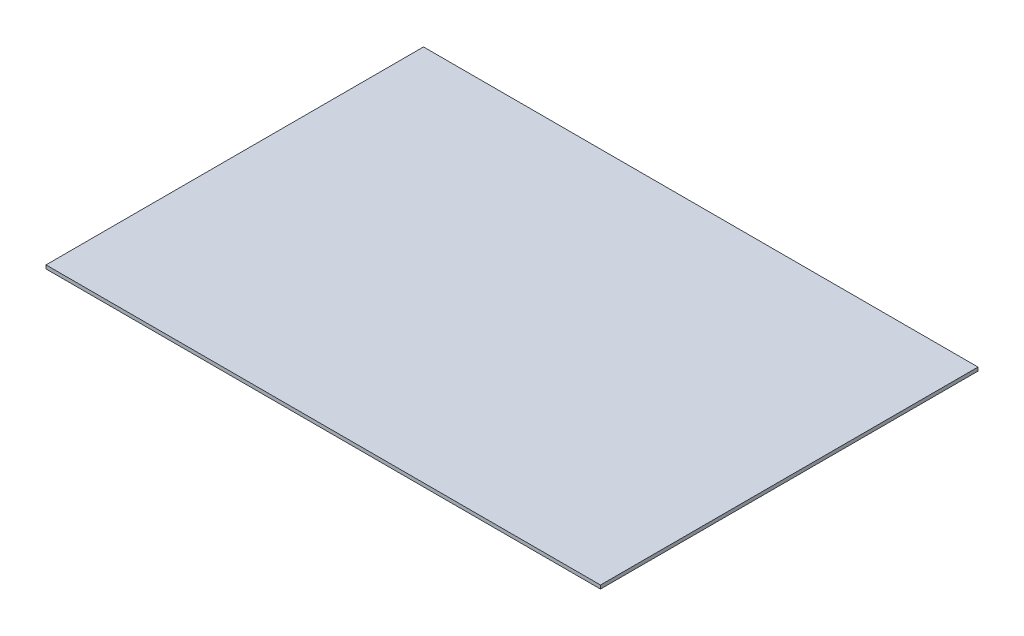
SolidWorks part; units mm, degrees
material "ABS PC"
ref_plane "Front Plane" through (0, 0, 0) normal (0, 0, 1) x (1, 0, 0)
ref_plane "Top Plane" through (0, 0, 0) normal (0, 1, 0) x (1, 0, 0)
ref_plane "Right Plane" through (0, 0, 0) normal (1, 0, 0) x (0, 0, -1)
sketch "Sketch1" plane through (0, 0, 0) normal (0, 1, 0) x (1, 0, 0)
  line L1 (0, 0) -> (940, 0)
  line L2 (0, 0) -> (0, 640)
  line L3 (0, 640) -> (940, 640)
  line L4 (940, 0) -> (940, 640)
  dimension "D1" = 640
  dimension "D2" = 940
extrude "Boss-Extrude1" add sketch "Sketch1" along normal blind 6
